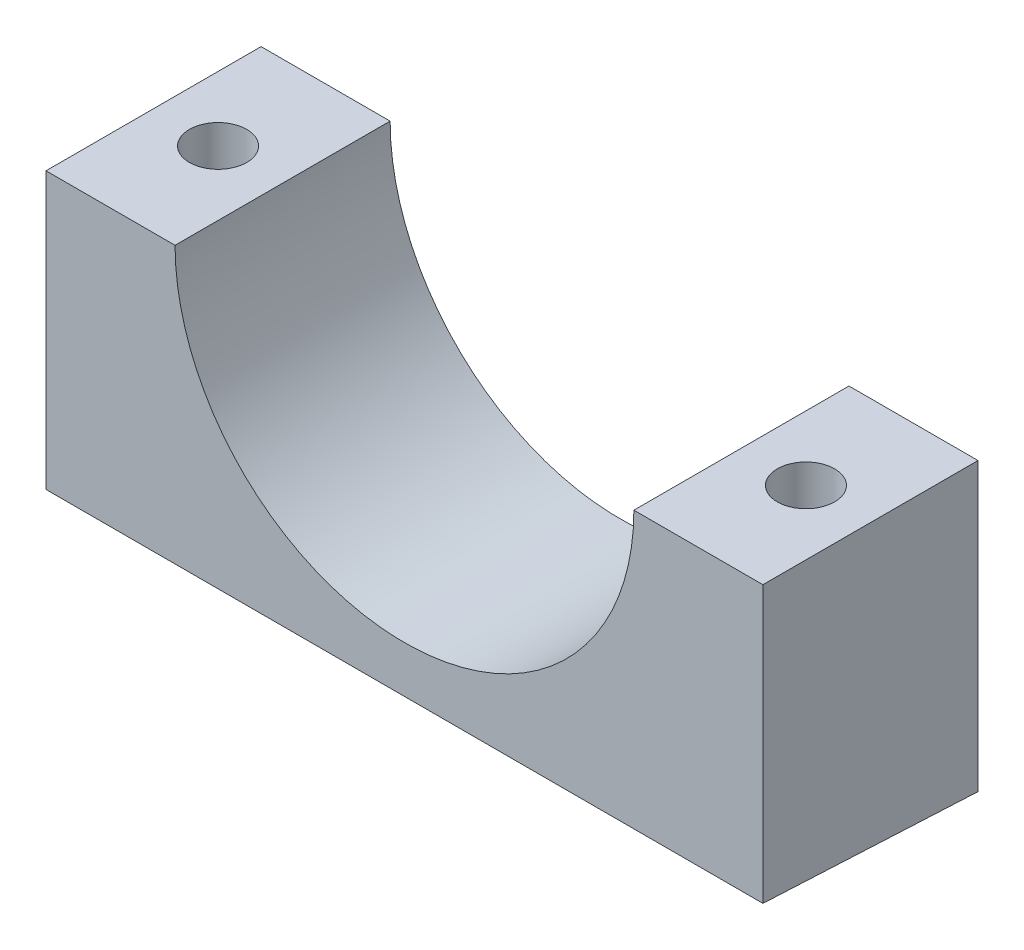
SolidWorks part; units mm, degrees
ref_plane "Front Plane" through (0, 0, 0) normal (0, 0, 1) x (1, 0, 0)
ref_plane "Top Plane" through (0, 0, 0) normal (0, 1, 0) x (1, 0, 0)
ref_plane "Right Plane" through (0, 0, 0) normal (1, 0, 0) x (0, 0, -1)
sketch "Sketch1" plane through (0, 0, 0) normal (0, 0, 1) x (1, 0, 0)
  line L1 (-25, -10) -> (25, -10)
  line L2 (-25, -10) -> (-25, 10)
  line L3 (-25, 10) -> (25, 10)
  line L4 (25, -10) -> (25, 10)
  line L5 (-25, -10) -> (25, 10) construction
  line L6 (-25, 10) -> (25, -10) construction
  point P0 (0, 0)
  dimension "D1" = 50
  dimension "D2" = 20
extrude "Boss-Extrude1" add sketch "Sketch1" along normal blind 15
sketch "Sketch2" plane through (25, 0, 0) normal (1, 0, 0) x (0, 0, -1)
  line L0 (0, -10) -> (-15, -9.25)
  line L1 (-15, -10) -> (-15, 10) construction
  line L2 (-15, -10) -> (0, -10) construction
  dimension "D1" = 2.862
extrude "Cut-Extrude1" cut sketch "Sketch2" against normal through all and the other way through all
sketch "Sketch3" plane through (0, 0, 0) normal (0, 0, -1) x (-1, 0, 0)
  line L0 (-25, 10) -> (25, 10) construction
  line L1 (-16, 10) -> (16, 10)
  arc A0 (-16, 10) -> (16, 10) centre (0, 10) ccw
  dimension "D1" = 16
extrude "Cut-Extrude2" cut sketch "Sketch3" against normal blind 15
sketch "Sketch4" plane through (0, 10, 0) normal (0, 1, 0) x (1, 0, 0)
  line L0 (20.5, 0) -> (20.5, -15) construction
  line L1 (25, 0) -> (16, 0) construction
  line L2 (25, -15) -> (16, -15) construction
  circle A0 centre (20.5, -7.5) radius 2
  point P8 (20.5, -7.5)
  dimension "D1" = 4
extrude "Cut-Extrude3" cut sketch "Sketch4" against normal blind 10
mirror "Mirror1" about plane through (0, 0, 0) normal (1, 0, 0) of "Cut-Extrude3"
equation "\"D1@Sketch2\"=atn(10/200deg)"
